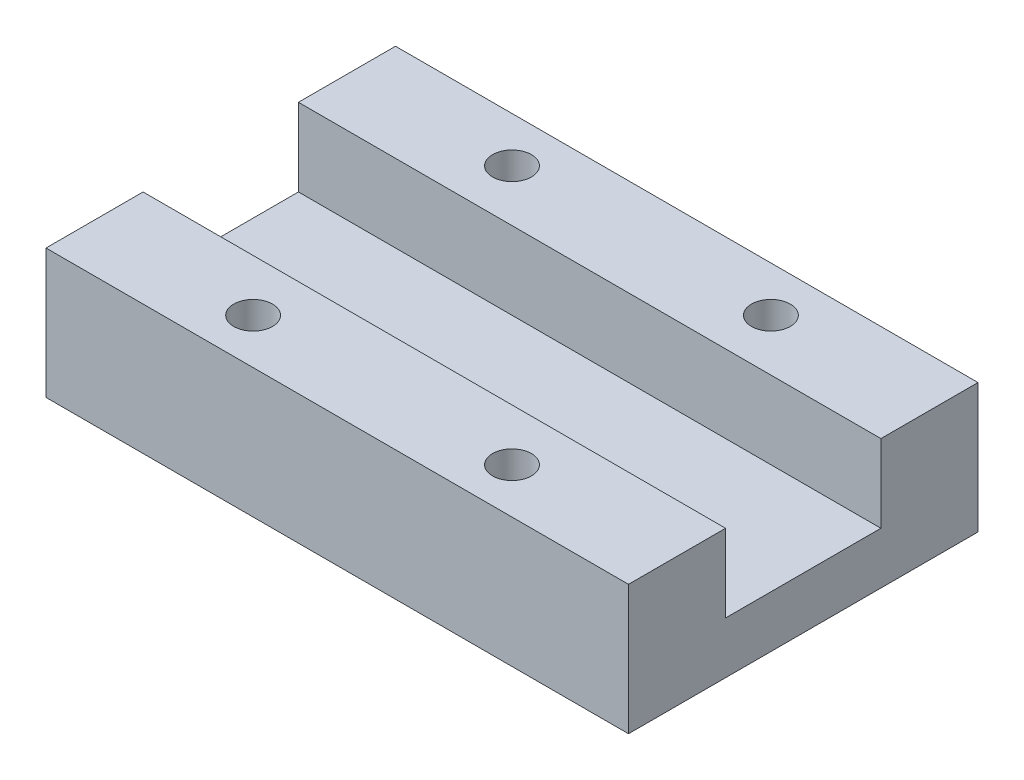
SolidWorks part; units mm, degrees
ref_plane "Front Plane" through (0, 0, 0) normal (0, 0, 1) x (1, 0, 0)
ref_plane "Top Plane" through (0, 0, 0) normal (0, 1, 0) x (1, 0, 0)
ref_plane "Right Plane" through (0, 0, 0) normal (1, 0, 0) x (0, 0, -1)
sketch "Sketch1" plane through (0, 0, 0) normal (1, 0, 0) x (0, 0, -1)
  line L0 (0, 0) -> (27, 0)
  line L1 (27, 0) -> (27, 10)
  line L2 (27, 10) -> (19.5, 10)
  line L3 (19.5, 10) -> (19.5, 4)
  line L4 (19.5, 4) -> (7.5, 4)
  line L5 (7.5, 4) -> (7.5, 10)
  line L6 (7.5, 10) -> (0, 10)
  line L7 (0, 10) -> (0, 0)
  dimension "D1" = 10
  dimension "D2" = 6
  dimension "D3" = 12
  dimension "D4" = 27
extrude "Boss-Extrude1" add sketch "Sketch1" along normal blind 45
sketch "Sketch2" plane through (0, 0, 0) normal (0, -1, 0) x (1, 0, 0)
  line L0 (45, -27) -> (0, -27) construction
  line L1 (12.5, -23.5) -> (32.5, -23.5)
  line L2 (12.5, -23.5) -> (12.5, -3.5)
  line L3 (12.5, -3.5) -> (32.5, -3.5)
  line L4 (32.5, -23.5) -> (32.5, -3.5)
  line L5 (12.5, -23.5) -> (32.5, -3.5) construction
  line L6 (12.5, -3.5) -> (32.5, -23.5) construction
  line L7 (0, 0) -> (0, -27) construction
  circle A0 centre (32.5, -23.5) radius 1.5
  circle A1 centre (32.5, -3.5) radius 1.5
  circle A2 centre (12.5, -3.5) radius 1.5
  circle A3 centre (12.5, -23.5) radius 1.5
  point P0 (22.5, -13.5)
  point P7 (22.5, -27)
  point P10 (0, -13.5)
  dimension "D2" = 3
  dimension "D1" = 20
extrude "Cut-Extrude1" cut sketch "Sketch2" against normal blind 45 contours L4 A1 L3 | L3 A1 L4 | L4 A0 L1 | L1 A0 L4 | L1 A3 L2 | L2 A3 L1 | L3 A2 L2 | L2 A2 L3
